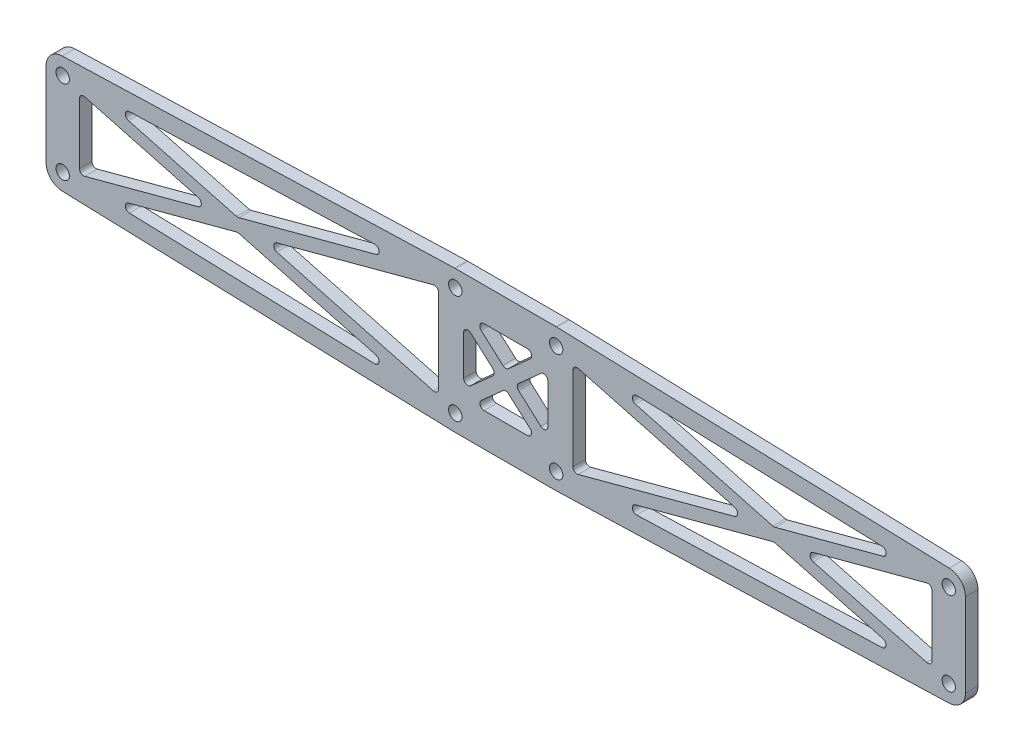
SolidWorks part; units mm, degrees
material "Thornel Mat VMA"
ref_plane "前视基准面" through (0, 0, 0) normal (0, 0, 1) x (1, 0, 0)
ref_plane "上视基准面" through (0, 0, 0) normal (0, 1, 0) x (1, 0, 0)
ref_plane "右视基准面" through (0, 0, 0) normal (1, 0, 0) x (0, 0, -1)
other "Configuration Table"
sketch "草图1" plane through (0, 0, 0) normal (0, 0, 1) x (1, 0, 0)
  line L1 (-31, -25) -> (31, -25) construction
  line L2 (-31, -25) -> (-31, 25) construction
  line L3 (-31, 25) -> (31, 25) construction
  line L4 (31, -25) -> (31, 25) construction
  line L5 (-31, -25) -> (31, 25) construction
  line L6 (-31, 25) -> (31, -25) construction
  line L7 (-110, -17) -> (110, -17)
  line L8 (-110, -17) -> (-110, 17)
  line L9 (-110, 17) -> (110, 17)
  line L10 (110, -17) -> (110, 17)
  line L11 (-110, -17) -> (110, 17) construction
  line L12 (-110, 17) -> (110, -17) construction
  line L13 (-12.07, 13) -> (12.07, 13) construction
  line L14 (-12.07, 13) -> (-12.07, -13) construction
  line L15 (-12.07, -13) -> (12.07, -13) construction
  line L16 (12.07, 13) -> (12.07, -13) construction
  line L17 (-12.07, 13) -> (12.07, -13) construction
  line L18 (-12.07, -13) -> (12.07, 13) construction
  circle A4 centre (-12.07, 13) radius 1.6 construction
  circle A5 centre (12.07, -13) radius 1.6 construction
  point P0 (0, 0)
  point P5 (0, 0)
  point P10 (0, 0)
  dimension "D3" = 24.14
  dimension "D7" = 3.2
  dimension "D1" = 62
  dimension "D2" = 50
  dimension "D4" = 4
  dimension "D5" = 220
  dimension "D6" = 26
extrude "凸台-拉伸1" add sketch "草图1" along normal blind 3
sketch "草图2" plane through (0, 0, 3) normal (0, 0, 1) x (1, 0, 0)
  line L1 (-12.07, -13) -> (12.07, -13) construction
  line L2 (-12.07, -13) -> (-12.07, 13) construction
  line L3 (-12.07, 13) -> (12.07, 13) construction
  line L4 (12.07, -13) -> (12.07, 13) construction
  line L5 (-12.07, -13) -> (12.07, 13) construction
  line L6 (-12.07, 13) -> (12.07, -13) construction
  circle A0 centre (-12.07, 13) radius 1.6
  circle A1 centre (12.07, 13) radius 1.6
  circle A2 centre (12.07, -13) radius 1.6
  circle A3 centre (-12.07, -13) radius 1.6
  point P0 (0, 0)
  dimension "D3" = 3.2
  dimension "D1" = 26
  dimension "D2" = 24.14
extrude "切除-拉伸1" cut sketch "草图2" against normal mid plane 10
sketch "草图3" plane through (0, 0, 3) normal (0, 0, 1) x (1, 0, 0)
  line L0 (-110, 0) -> (110, 0) construction
  line L1 (-110, 17) -> (-110, -17) construction
  line L2 (110, -17) -> (110, 17) construction
  line L3 (-106, 10) -> (-106, -10) construction
  line L4 (106, 10) -> (106, -10) construction
  line L5 (0, 0) -> (0, -50000) construction
  line L6 (110, 17) -> (-110, 17) construction
  line L7 (-106.1277, 13.998) -> (-12.1977, 16.998)
  line L8 (-110, 10) -> (-110, -10) construction
  line L9 (-106.1277, -13.998) -> (-12.1977, -16.998)
  line L14 (110, -17) -> (110, 17)
  line L15 (110, 17) -> (-110, 17)
  line L16 (-110, 17) -> (-110, -17)
  line L17 (-110, -17) -> (110, -17)
  line L18 (110, -17) -> (110, 17)
  line L19 (110, 17) -> (-110, 17)
  line L20 (-110, 17) -> (-110, -17)
  line L21 (-110, -17) -> (110, -17)
  circle A0 centre (-106, 10) radius 1.6
  circle A1 centre (-106, -10) radius 1.6
  circle A2 centre (106, 10) radius 1.6
  circle A3 centre (106, -10) radius 1.6
  circle A4 centre (-12.07, 13) radius 4
  circle A5 centre (-106, 10) radius 4
  circle A6 centre (-106, -10) radius 4
  circle A7 centre (-12.07, -13) radius 4
  circle A8 centre (-106, -10) radius 1.6
  point P9 (-106, 0)
  point P12 (106, 0)
  point P14 (0, 0)
  line M7 (-110, 17) -> (-110, -17)
  line M8 (-110, -17) -> (110, -17)
  dimension "D4" = 3.2
  dimension "D2" = 20
  dimension "D1" = 4
  dimension "D3" = 4
  dimension "D5" = 0
extrude "切除-拉伸3" cut sketch "草图3" against normal mid plane 10 contours A5 L7 A4 L19 M7 | A7 L9 A6 M8 M7 | A1 | A0
mirror "镜向1" about plane through (0, 0, 0) normal (1, 0, 0) of "切除-拉伸3"
sketch "草图4" plane through (0, 0, 3) normal (0, 0, 1) x (1, 0, 0)
  line L0 (12.07, 17) -> (-12.07, 17) construction
  line L1 (-10.07, -9) -> (10.07, -9)
  line L2 (-10.07, -9) -> (-10.07, 9)
  line L3 (-10.07, 9) -> (10.07, 9)
  line L4 (10.07, -9) -> (10.07, 9)
  line L5 (-10.07, -9) -> (10.07, 9) construction
  line L6 (-10.07, 9) -> (10.07, -9) construction
  line L7 (-12.07, 13) -> (-12.07, -13) construction
  line L8 (0, 0) -> (50000, 0) construction
  line L9 (0, 0) -> (0, -50000) construction
  line L10 (-16.07, 12.8722) -> (-102, 10.1278)
  line L11 (-102, 10.1278) -> (-102, -10.1278)
  line L12 (-102, -10.1278) -> (-16.07, -12.8722)
  line L13 (-16.07, -12.8722) -> (-16.07, 12.8722)
  line L14 (-110, 10) -> (-110, -10) construction
  line L15 (-12.1977, 16.998) -> (-106.1277, 13.998) construction
  line L16 (-102, 10.1278) -> (-16.07, -12.8722) construction
  line L17 (-102, -10.1278) -> (-16.07, 12.8722) construction
  line L18 (-101.6122, -11.5767) -> (-15.6822, 11.4233)
  line L19 (-102.3878, 8.6788) -> (-16.4578, -14.3212)
  line L20 (-11.0696, 7.8816) -> (9.0704, -10.1184)
  line L21 (-9.0704, -10.1184) -> (11.0696, 7.8816)
  line L22 (-102.3878, -8.6788) -> (-16.4578, 14.3212)
  line L23 (-101.6122, 11.5767) -> (-15.6822, -11.4233)
  line L24 (-9.0704, 10.1184) -> (11.0696, -7.8816)
  line L25 (-11.0696, -7.8816) -> (9.0704, 10.1184)
  line L26 (102, -10.1278) -> (16.07, 12.8722) construction
  line L27 (102, 10.1278) -> (16.07, -12.8722) construction
  line L28 (0, 0) -> (-50000, 0) construction
  line L29 (101.6122, 11.5767) -> (15.6822, -11.4233)
  line L30 (102.3878, -8.6788) -> (16.4578, 14.3212)
  line L31 (102.3878, 8.6788) -> (16.4578, -14.3212)
  line L32 (101.6122, -11.5767) -> (15.6822, 11.4233)
  line L33 (102, -10.1278) -> (16.07, -12.8722)
  line L34 (102, 10.1278) -> (102, -10.1278)
  line L35 (16.07, 12.8722) -> (102, 10.1278)
  line L36 (16.07, 12.8722) -> (16.07, -12.8722)
  point P0 (0, 0)
  dimension "D1" = 8
  dimension "D2" = 4
  dimension "D3" = 8
  dimension "D4" = 4
  dimension "D5" = 4
  dimension "D6" = 1.5
  dimension "D7" = 1.5
extrude "切除-拉伸4" cut sketch "草图4" against normal mid plane 10 contours L18 L23 L13 | L10 L23 L22 | L11 L22 L19 | L19 L18 L12 | L2 L25 L20 | L24 L25 L3 | L21 L24 L4 | L21 L1 L20 | L32 L36 L29 | L35 L30 L29 | L34 L31 L30 | L33 L32 L31
fillet "圆角1" radius 1 36 edges at (10.07, -6.9882, 1.5) (2.251, 0, 1.5) (10.07, 6.9882, 1.5) (7.819, -9, 1.5) (-7.819, -9, 1.5) (0, -2.0118, 1.5) (-96.8171, -10.2933, 1.5) (-64.1618, -1.5528, 1.5) (-22.6575, -12.6619, 1.5) (-2.251, 0, 1.5) (-10.07, -6.9882, 1.5) (-10.07, 6.9882, 1.5) (64.1618, -1.5528, 1.5) (96.8171, -10.2933, 1.5) (22.6575, -12.6619, 1.5) (64.1618, 1.5528, 1.5) (22.6575, 12.6619, 1.5) (96.8171, 10.2933, 1.5) (69.9632, 0, 1.5) (102, 8.575, 1.5) (102, -8.575, 1.5) (-16.07, -11.3194, 1.5) (-58.3604, 0, 1.5) (-16.07, 11.3194, 1.5) (-22.6575, 12.6619, 1.5) (-64.1618, 1.5528, 1.5) (-96.8171, 10.2933, 1.5) (-102, 8.575, 1.5) (-69.9632, 0, 1.5) (-102, -8.575, 1.5) (58.3604, 0, 1.5) (16.07, -11.3194, 1.5) (-7.819, 9, 1.5) (7.819, 9, 1.5) (0, 2.0118, 1.5) (16.07, 11.3194, 1.5)
